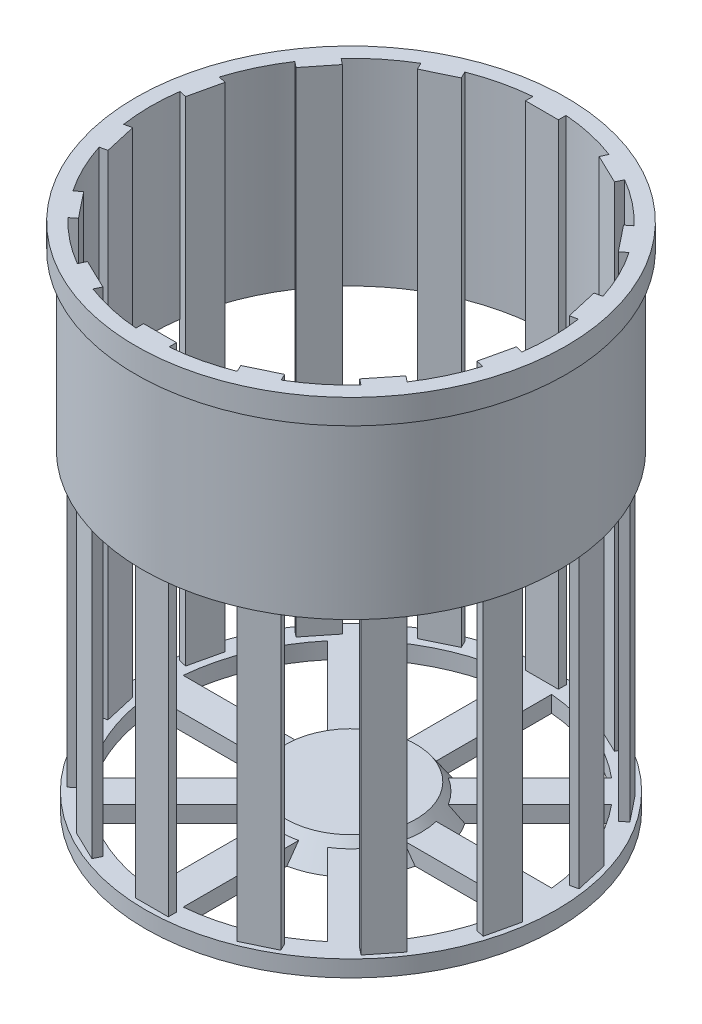
SolidWorks part; units mm, degrees
ref_plane "Спереди" through (0, 0, 0) normal (0, 0, 1) x (1, 0, 0)
ref_plane "Сверху" through (0, 0, 0) normal (0, 1, 0) x (1, 0, 0)
ref_plane "Справа" through (0, 0, 0) normal (1, 0, 0) x (0, 0, -1)
sketch "Эскиз1" plane through (0, 0, 0) normal (0, 1, 0) x (1, 0, 0)
  circle A0 centre (0, 0) radius 10
  dimension "D1" = 20
extrude "Бобышка-Вытянуть1" add sketch "Эскиз1" along normal blind 3 draft 35
sketch "Эскиз2" plane through (0, 0, 0) normal (0, -1, 0) x (1, 0, 0)
  line L1 (-2, 7) -> (2, 7)
  line L2 (-2, 7) -> (-2, 24)
  line L3 (-2, 24) -> (2, 24)
  line L4 (2, 7) -> (2, 24)
  point P4 (0, 7)
  dimension "D1" = 4
  dimension "D2" = 17
  dimension "D3" = 7
extrude "Бобышка-Вытянуть2" add sketch "Эскиз2" against normal blind 2
pattern_circular "Круговой массив1" count 8 over 360 about axis through (0, 0, 0) along (0, 1, 0) of "Бобышка-Вытянуть2"
sketch "Эскиз3" plane through (0, 0, 0) normal (0, 1, 0) x (1, 0, 0)
  circle A0 centre (0, 0) radius 22.5
  circle A1 centre (0, 0) radius 25
  dimension "D1" = 45
  dimension "D2" = 50
extrude "Бобышка-Вытянуть3" add sketch "Эскиз3" along normal blind 2
sketch "Эскиз5" plane through (0, 2, 0) normal (0, 1, 0) x (1, 0, 0)
  line L1 (-2.1223, 24.353) -> (1.8777, 24.353)
  line L2 (-2.1223, 24.353) -> (-2.1223, 23.353)
  line L3 (-2.1223, 23.353) -> (1.8777, 23.353)
  line L4 (1.8777, 24.353) -> (1.8777, 23.353)
  circle A2 centre (0, 0) radius 25 construction
  point P4 (2, 24.646)
  point P5 (0, 0)
  point P7 (-1.1512, 22.4109)
  point P8 (0, 0)
  point P10 (2, 24.9199)
  point P11 (2, 24.7495)
  point P12 (2, 24.7947)
  dimension "D1" = 1
  dimension "D2" = 0.95
  dimension "D3" = 4
  dimension "D4" = 24.353
extrude "Бобышка-Вытянуть4" add sketch "Эскиз5" along normal blind 60
pattern_circular "Круговой массив2" count 14 over 360 about axis through (0, 0, 0) along (0, 1, 0) of "Бобышка-Вытянуть4"
sketch "Эскиз8" plane through (0, 62, 0) normal (0, 1, 0) x (1, 0, 0)
  circle A0 centre (0, 0) radius 24.353
extrude "Вытянуть-Тонкостенный1" add sketch "Эскиз8" against normal blind 24 thin
sketch "Эскиз9" plane through (0, 62, 0) normal (0, 1, 0) x (1, 0, 0)
  circle A0 centre (0, 0) radius 25.183
  dimension "D1" = 50.366
extrude "Вытянуть-Тонкостенный2" add sketch "Эскиз9" against normal blind 3 thin
